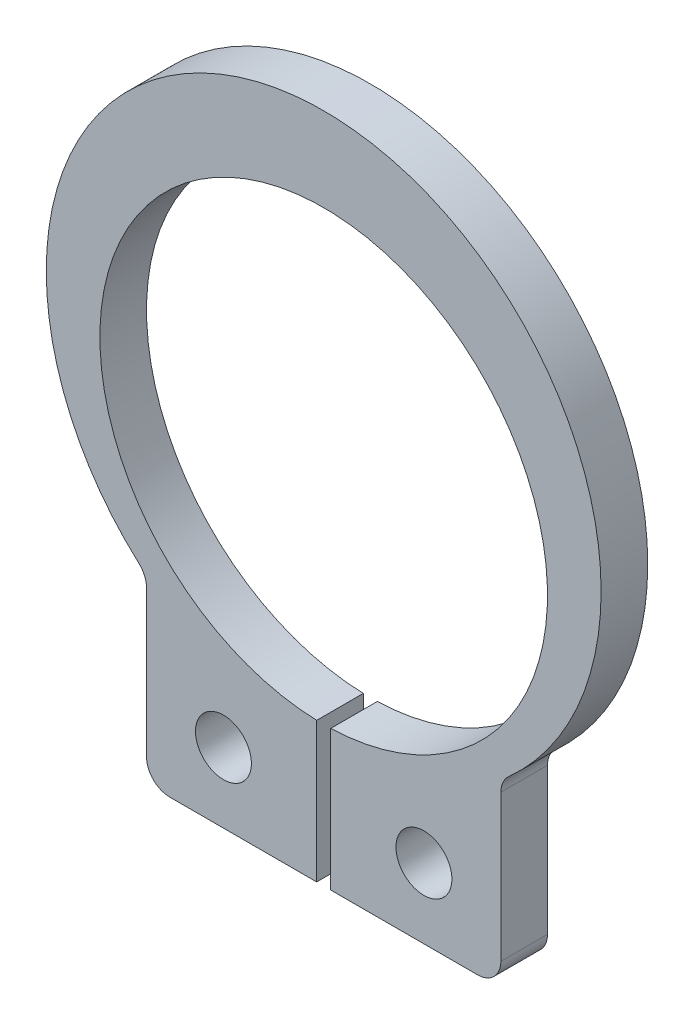
SolidWorks part; units mm, degrees
ref_plane "Front Plane" through (0, 0, 0) normal (0, 0, 1) x (1, 0, 0)
ref_plane "Top Plane" through (0, 0, 0) normal (0, 1, 0) x (1, 0, 0)
ref_plane "Right Plane" through (0, 0, 0) normal (1, 0, 0) x (0, 0, -1)
sketch "Sketch1" plane through (0, 0, 0) normal (0, 0, 1) x (1, 0, 0)
  line L0 (-3.8, -4.1575) -> (-3.8, -7.3)
  line L1 (-3.3, -7.8) -> (-0.15, -7.8)
  line L5 (-0.15, -7.8) -> (-0.15, -4.7977)
  line L6 (0.15, -4.7977) -> (0.15, -7.8)
  line L10 (0.15, -7.8) -> (3.3, -7.8)
  line L11 (3.8, -7.3) -> (3.8, -4.1575)
  line L12 (0, 0) -> (0, 6.6) construction
  arc A0 (3.9667, -3.7849) -> (-3.9667, -3.7849) centre (0, 0.65) ccw
  arc A1 (-3.9667, -3.7849) -> (-3.8, -4.1575) centre (-4.3, -4.1575) cw
  arc A2 (-3.8, -7.3) -> (-3.3, -7.8) centre (-3.3, -7.3) ccw
  arc A4 (-0.15, -4.7977) -> (0.15, -4.7977) centre (0, 0) cw
  arc A6 (3.3, -7.8) -> (3.8, -7.3) centre (3.3, -7.3) ccw
  arc A7 (3.8, -4.1575) -> (3.9667, -3.7849) centre (4.3, -4.1575) cw
  dimension "D1" = 0.3
  dimension "REC_D2_s" = 9.6
  dimension "D2" = 0.5
  dimension "D4" = 0.65
  dimension "REC_MSM_1" = 11.9
  dimension "D3" = 0.5
  dimension "REC_MSM_2" = 7.6
  dimension "REC_A_s" = 3
  dimension "REC_B_s" = 1.8
extrude "Boss-Extrude1" add sketch "Sketch1" against normal blind 1
sketch "Sketch2" plane through (0, 0, 0) normal (0, 0, 1) x (1, 0, 0)
  line L0 (-3.8, -6.3) -> (3.8, -6.3) construction
  line L1 (-3.8, -4.1575) -> (-3.8, -7.3) construction
  line L2 (3.8, -7.3) -> (3.8, -4.1575) construction
  line L3 (-3.3, -7.8) -> (-0.15, -7.8) construction
  line L4 (0, 0) -> (0, -7.8) construction
  circle A0 centre (-2.15, -6.3) radius 0.6
  circle A1 centre (2.15, -6.3) radius 0.6
  dimension "REC_D0_s" = 1.2
  dimension "REC_MSM_4" = 1.5
  dimension "REC_MSM_3" = 4.3
extrude "Cut-Extrude1" cut sketch "Sketch2" against normal through all
